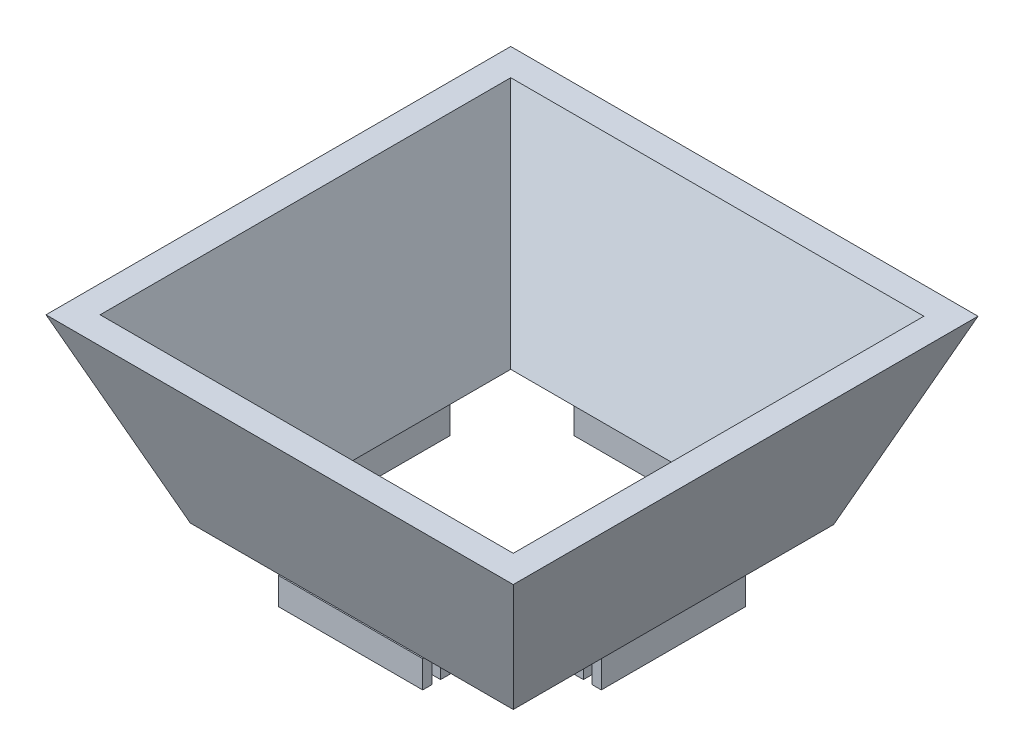
SolidWorks part; units mm, degrees
ref_plane "Front Plane" through (0, 0, 0) normal (0, 0, 1) x (1, 0, 0)
ref_plane "Top Plane" through (0, 0, 0) normal (0, 1, 0) x (1, 0, 0)
ref_plane "Right Plane" through (0, 0, 0) normal (1, 0, 0) x (0, 0, -1)
sketch "Sketch1" plane through (0, 0, 0) normal (0, 1, 0) x (1, 0, 0)
  line L1 (0, 0) -> (227.33, 0)
  line L2 (0, 0) -> (0, 225.552)
  line L3 (0, 225.552) -> (227.33, 225.552)
  line L4 (227.33, 0) -> (227.33, 225.552)
  dimension "D1" = 227.33
  dimension "D2" = 225.552
ref_plane "Plane1" through (0, 127, 0) normal (0, 1, 0) x (1, 0, 0)
sketch "Sketch2" plane through (0, 127, 0) normal (0, 1, 0) x (1, 0, 0)
  line L8 (-50.8, -50.8) -> (278.13, -50.8)
  line L9 (278.13, -50.8) -> (278.13, 276.352)
  line L10 (278.13, 276.352) -> (-50.8, 276.352)
  line L11 (-50.8, 276.352) -> (-50.8, -50.8)
  line L12 (-50.8, -50.8) -> (278.13, -50.8)
  line L13 (278.13, -50.8) -> (278.13, 276.352)
  line L14 (278.13, 276.352) -> (-50.8, 276.352)
  line L15 (-50.8, 276.352) -> (-50.8, -50.8)
  dimension "D1" = 50.8
loft "Loft1" add profiles "Sketch2" section "Sketch2" section "Sketch1"
sketch "Sketch3" plane through (0, 127, 0) normal (0, 1, 0) x (1, 0, 0)
  line L8 (-31.75, 257.302) -> (-31.75, -31.75)
  line L9 (-31.75, -31.75) -> (259.08, -31.75)
  line L10 (259.08, -31.75) -> (259.08, 257.302)
  line L11 (259.08, 257.302) -> (-31.75, 257.302)
  line L12 (-31.75, 257.302) -> (-31.75, -31.75)
  line L13 (-31.75, -31.75) -> (259.08, -31.75)
  line L14 (259.08, -31.75) -> (259.08, 257.302)
  line L15 (259.08, 257.302) -> (-31.75, 257.302)
  dimension "D1" = 19.05
sketch "Sketch4" plane through (0, 0, 0) normal (0, -1, 0) x (1, 0, 0)
  line L8 (208.28, -19.05) -> (19.05, -19.05)
  line L9 (19.05, -19.05) -> (19.05, -206.502)
  line L10 (19.05, -206.502) -> (208.28, -206.502)
  line L11 (208.28, -206.502) -> (208.28, -19.05)
  line L12 (208.28, -19.05) -> (19.05, -19.05)
  line L13 (19.05, -19.05) -> (19.05, -206.502)
  line L14 (19.05, -206.502) -> (208.28, -206.502)
  line L15 (208.28, -206.502) -> (208.28, -19.05)
  dimension "D1" = 19.05
loft "Cut-Loft3" cut profiles "Sketch3" section "Sketch4" section "Sketch3"
sketch "Sketch5" plane through (0, 0, 0) normal (0, -1, 0) x (1, 0, 0)
  line L0 (0, -61.976) -> (6.477, -61.976)
  line L5 (0, -61.976) -> (0, -163.576)
  line L6 (0, 0) -> (0, -225.552) construction
  line L7 (6.477, -61.976) -> (6.477, -163.576)
  line L8 (6.477, -163.576) -> (0, -163.576)
  line L9 (19.05, -61.976) -> (19.05, -163.576)
  line L10 (19.05, -19.05) -> (19.05, -206.502) construction
  line L11 (19.05, -61.976) -> (12.573, -61.976)
  line L12 (12.573, -61.976) -> (12.573, -163.576)
  line L13 (12.573, -163.576) -> (19.05, -163.576)
  line L14 (19.05, -19.05) -> (208.28, -206.502) construction
  line L15 (164.465, -5.588) -> (62.865, -5.588)
  line L16 (164.465, 0.889) -> (62.865, 0.889)
  line L17 (164.465, 0.889) -> (164.465, -5.588)
  line L18 (62.865, -5.588) -> (62.865, 0.889)
  line L19 (164.465, -11.684) -> (62.865, -11.684)
  line L20 (164.465, -18.161) -> (62.865, -18.161)
  line L21 (164.465, -18.161) -> (164.465, -11.684)
  line L22 (62.865, -11.684) -> (62.865, -18.161)
  line L23 (220.853, -163.576) -> (220.853, -61.976)
  line L24 (227.33, -163.576) -> (227.33, -61.976)
  line L25 (227.33, -163.576) -> (220.853, -163.576)
  line L26 (220.853, -61.976) -> (227.33, -61.976)
  line L27 (214.757, -163.576) -> (214.757, -61.976)
  line L28 (208.28, -163.576) -> (208.28, -61.976)
  line L29 (208.28, -163.576) -> (214.757, -163.576)
  line L30 (214.757, -61.976) -> (208.28, -61.976)
  line L31 (62.865, -219.964) -> (164.465, -219.964)
  line L32 (62.865, -226.441) -> (164.465, -226.441)
  line L33 (62.865, -226.441) -> (62.865, -219.964)
  line L34 (164.465, -219.964) -> (164.465, -226.441)
  line L35 (62.865, -213.868) -> (164.465, -213.868)
  line L36 (62.865, -207.391) -> (164.465, -207.391)
  line L37 (62.865, -207.391) -> (62.865, -213.868)
  line L38 (164.465, -213.868) -> (164.465, -207.391)
  point P5 (0, -112.776)
  point P12 (19.05, -112.776)
  point P14 (113.665, -112.776)
  point P15 (0, 0)
  point P16 (0, 0)
  point P46 (113.665, -112.776)
  dimension "D1" = 101.6
  dimension "D2" = 6.096
  dimension "D3" = 4
extrude "Boss-Extrude1" add sketch "Sketch5" along normal blind 19.05
